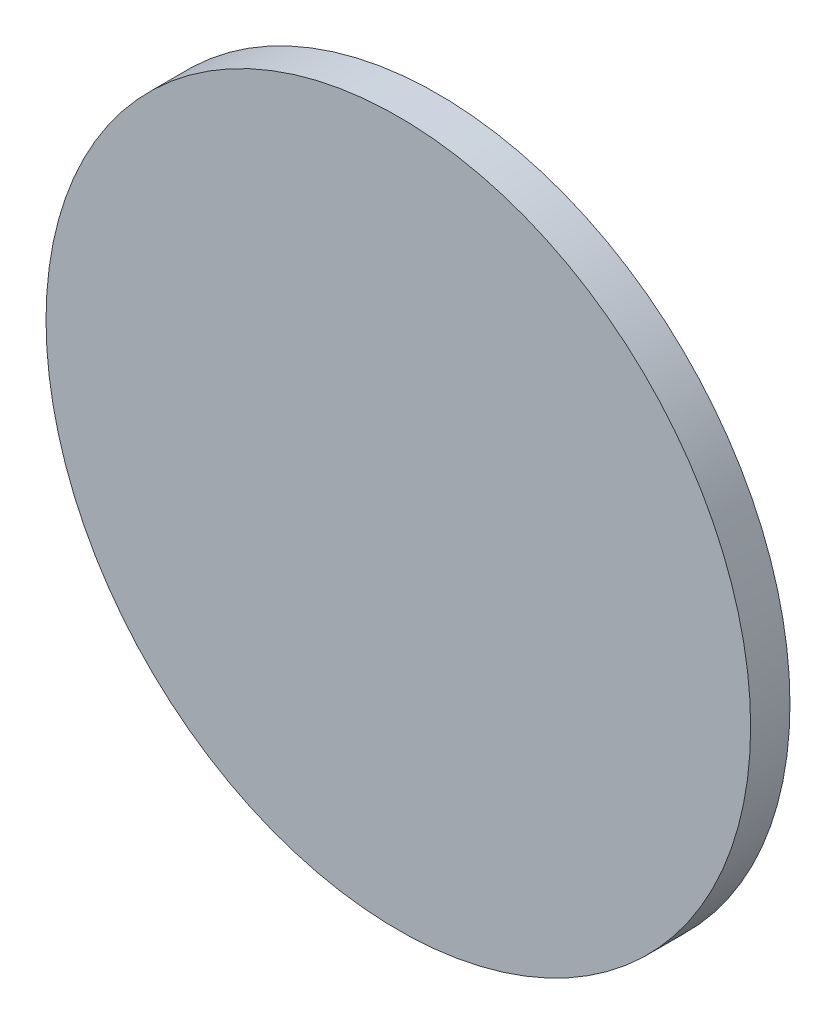
SolidWorks part; units mm, degrees
ref_plane "Front Plane" through (0, 0, 0) normal (0, 0, 1) x (1, 0, 0)
ref_plane "Top Plane" through (0, 0, 0) normal (0, 1, 0) x (1, 0, 0)
ref_plane "Right Plane" through (0, 0, 0) normal (1, 0, 0) x (0, 0, -1)
sketch "Sketch1" plane through (0, 0, 0) normal (0, 0, 1) x (1, 0, 0)
  circle A0 centre (0, 0) radius 22.75
  dimension "D1" = 45.5
extrude "Boss-Extrude1" add sketch "Sketch1" along normal blind 2.54
